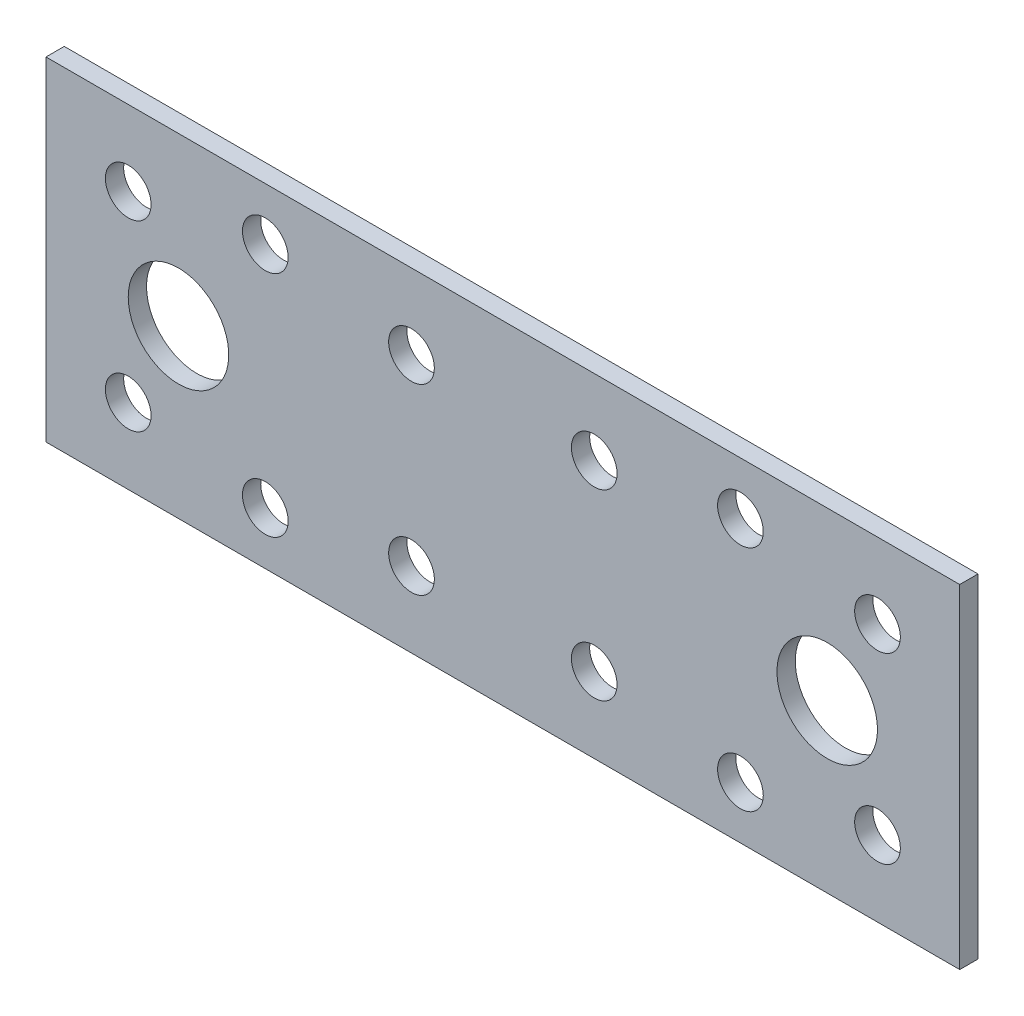
SolidWorks part; units mm, degrees
ref_plane "Спереди" through (0, 0, 0) normal (0, 0, 1) x (1, 0, 0)
ref_plane "Сверху" through (0, 0, 0) normal (0, 1, 0) x (1, 0, 0)
ref_plane "Справа" through (0, 0, 0) normal (1, 0, 0) x (0, 0, -1)
sketch "Эскиз1" plane through (0, 0, 0) normal (0, 0, 1) x (1, 0, 0)
  line L0 (0, 0) -> (0, 33.0426) construction
  line L1 (0, 0) -> (32.0019, 0) construction
  line L2 (-41, 10) -> (-13.9429, 10) construction
  line L3 (-50, -18.25) -> (50, -18.25)
  line L4 (-50, -18.25) -> (-50, 18.25)
  line L5 (-50, 18.25) -> (50, 18.25)
  line L6 (50, -18.25) -> (50, 18.25)
  circle A0 centre (35.5, 0) radius 5.5
  circle A1 centre (-35.5, 0) radius 5.5
  circle A2 centre (-41, 10) radius 2.5
  circle A3 centre (-26, 12.5) radius 2.5
  circle A4 centre (-10, 10) radius 2.5
  circle A5 centre (-10, -10) radius 2.5
  circle A6 centre (-26, -12.5) radius 2.5
  circle A7 centre (-41, -10) radius 2.5
  circle A8 centre (10, 10) radius 2.5
  circle A9 centre (10, -10) radius 2.5
  circle A10 centre (26, -12.5) radius 2.5
  circle A11 centre (26, 12.5) radius 2.5
  circle A12 centre (41, 10) radius 2.5
  circle A13 centre (41, -10) radius 2.5
  dimension "D3" = 11
  dimension "D4" = 35.5
  dimension "D5" = 10
  dimension "D6" = 5
  dimension "D8" = 31
  dimension "D9" = 12.5
  dimension "D11" = 25
  dimension "D12" = 52
  dimension "D7" = 82
  dimension "D1" = 100
  dimension "D2" = 36.5
  dimension "D10" = 24
extrude "Вытянуть1" add sketch "Эскиз1" along normal blind 2
